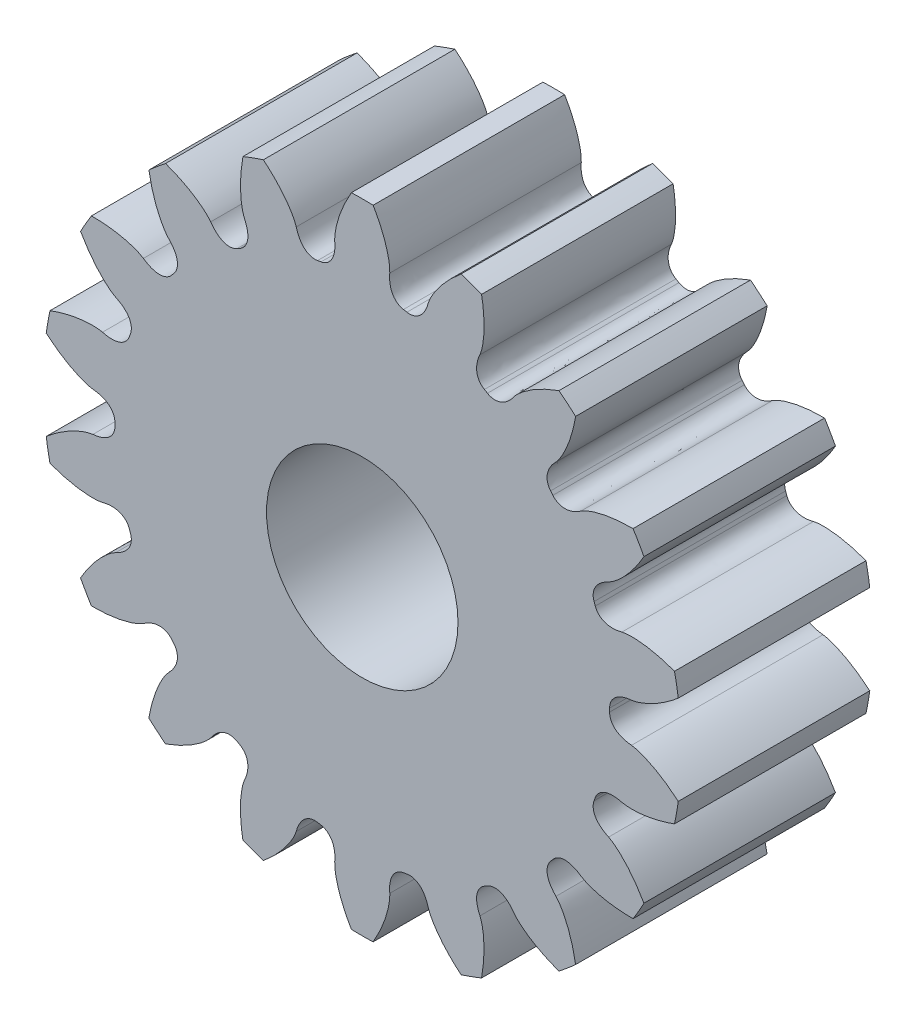
SolidWorks part; units mm, degrees
ref_plane "Спереди" through (0, 0, 0) normal (0, 0, 1) x (1, 0, 0)
ref_plane "Сверху" through (0, 0, 0) normal (0, 1, 0) x (1, 0, 0)
ref_plane "Справа" through (0, 0, 0) normal (1, 0, 0) x (0, 0, -1)
sketch "Model" plane through (0, 0, 0) normal (0, 0, 1) x (1, 0, 0)
  line L0 (-7.7, 0) -> (7.7, 0) construction
  line L1 (0, -7.7) -> (0, 7.7) construction
  arc A0 (0.1704, 4.9971) -> (-0.1704, 4.9971) centre (0, 0) ccw
  arc A1 (-0.6456, 3.8208) -> (-0.7002, 3.8112) centre (0, 0) ccw
  arc A2 (-1.549, 4.754) -> (-1.8692, 4.6375) centre (0, 0) ccw
  arc A3 (-1.9135, 3.3696) -> (-1.9614, 3.3419) centre (0, 0) ccw
  arc A4 (-3.0816, 3.9375) -> (-3.3426, 3.7185) centre (0, 0) ccw
  arc A5 (-2.9505, 2.512) -> (-2.9862, 2.4695) centre (0, 0) ccw
  arc A6 (-4.2424, 2.6461) -> (-4.4128, 2.351) centre (0, 0) ccw
  arc A7 (-3.6317, 1.3513) -> (-3.6507, 1.2993) centre (0, 0) ccw
  arc A8 (-4.8916, 1.0355) -> (-4.9508, 0.6999) centre (0, 0) ccw
  arc A9 (-3.8749, 0.0277) -> (-3.8749, -0.0277) centre (0, 0) ccw
  arc A10 (-4.9508, -0.6999) -> (-4.8916, -1.0355) centre (0, 0) ccw
  arc A11 (-3.6507, -1.2993) -> (-3.6317, -1.3513) centre (0, 0) ccw
  arc A12 (-4.4128, -2.351) -> (-4.2424, -2.6461) centre (0, 0) ccw
  arc A13 (-2.9862, -2.4695) -> (-2.9505, -2.512) centre (0, 0) ccw
  arc A14 (-3.3426, -3.7185) -> (-3.0816, -3.9375) centre (0, 0) ccw
  arc A15 (-1.9614, -3.3419) -> (-1.9135, -3.3696) centre (0, 0) ccw
  arc A16 (-1.8692, -4.6375) -> (-1.549, -4.754) centre (0, 0) ccw
  arc A17 (-0.7002, -3.8112) -> (-0.6456, -3.8208) centre (0, 0) ccw
  arc A18 (-0.1704, -4.9971) -> (0.1704, -4.9971) centre (0, 0) ccw
  arc A19 (0.6456, -3.8208) -> (0.7002, -3.8112) centre (0, 0) ccw
  arc A20 (1.549, -4.754) -> (1.8692, -4.6375) centre (0, 0) ccw
  arc A21 (1.9135, -3.3696) -> (1.9614, -3.3419) centre (0, 0) ccw
  arc A22 (3.0816, -3.9375) -> (3.3426, -3.7185) centre (0, 0) ccw
  arc A23 (2.9505, -2.512) -> (2.9862, -2.4695) centre (0, 0) ccw
  arc A24 (4.2424, -2.6461) -> (4.4128, -2.351) centre (0, 0) ccw
  arc A25 (3.6317, -1.3513) -> (3.6507, -1.2993) centre (0, 0) ccw
  arc A26 (4.8916, -1.0355) -> (4.9508, -0.6999) centre (0, 0) ccw
  arc A27 (3.8749, -0.0277) -> (3.8749, 0.0277) centre (0, 0) ccw
  arc A28 (4.9508, 0.6999) -> (4.8916, 1.0355) centre (0, 0) ccw
  arc A29 (3.6507, 1.2993) -> (3.6317, 1.3513) centre (0, 0) ccw
  arc A30 (4.4128, 2.351) -> (4.2424, 2.6461) centre (0, 0) ccw
  arc A31 (2.9862, 2.4695) -> (2.9505, 2.512) centre (0, 0) ccw
  arc A32 (3.3426, 3.7185) -> (3.0816, 3.9375) centre (0, 0) ccw
  arc A33 (1.9614, 3.3419) -> (1.9135, 3.3696) centre (0, 0) ccw
  arc A34 (1.8692, 4.6375) -> (1.549, 4.754) centre (0, 0) ccw
  arc A35 (0.7002, 3.8112) -> (0.6456, 3.8208) centre (0, 0) ccw
  circle A36 centre (0, 0) radius 4.5 construction
  spline S0 degree 3 poles (0.4314, 4.2073) (0.4264, 4.1628) (0.4271, 4.1189) (0.4335, 4.0758) (0.4372, 4.0511) (0.4421, 4.026) (0.4501, 4.0023) (0.4558, 3.9851) (0.4628, 3.968) (0.4713, 3.952) (0.4783, 3.9388) (0.4864, 3.9259) (0.4954, 3.914) (0.5034, 3.9034) (0.5123, 3.8933) (0.5218, 3.8841) (0.5307, 3.8755) (0.5403, 3.8675) (0.5504, 3.8604) (0.56, 3.8536) (0.5702, 3.8474) (0.5807, 3.8421) (0.5909, 3.837) (0.6017, 3.8326) (0.6125, 3.829) (0.6233, 3.8255) (0.6343, 3.8228) (0.6456, 3.8208) knots 0 0 0 0 1 1 1 2 2 2 3 3 3 4 4 4 5 5 5 6 6 6 7 7 7 8 8 8 9 9 9 9
  spline S1 degree 3 poles (-0.4314, 4.2073) (-0.4264, 4.1628) (-0.4271, 4.1189) (-0.4335, 4.0758) (-0.4372, 4.0511) (-0.4421, 4.026) (-0.4501, 4.0023) (-0.4558, 3.9851) (-0.4628, 3.968) (-0.4713, 3.952) (-0.4783, 3.9388) (-0.4864, 3.9259) (-0.4954, 3.914) (-0.5034, 3.9034) (-0.5123, 3.8933) (-0.5218, 3.8841) (-0.5307, 3.8755) (-0.5403, 3.8675) (-0.5504, 3.8604) (-0.56, 3.8536) (-0.5702, 3.8474) (-0.5807, 3.8421) (-0.5909, 3.837) (-0.6017, 3.8326) (-0.6125, 3.829) (-0.6233, 3.8255) (-0.6343, 3.8228) (-0.6456, 3.8208) knots 0 0 0 0 1 1 1 2 2 2 3 3 3 4 4 4 5 5 5 6 6 6 7 7 7 8 8 8 9 9 9 9
  spline S2 degree 3 poles (0.4314, 4.2073) (0.432, 4.2362) (0.431, 4.265) (0.4284, 4.2936) (0.4258, 4.3229) (0.4209, 4.352) (0.4156, 4.3809) (0.4101, 4.4104) (0.4034, 4.4397) (0.3959, 4.4687) (0.3884, 4.4983) (0.3797, 4.5277) (0.3705, 4.5568) (0.361, 4.5865) (0.3507, 4.6159) (0.3398, 4.6451) (0.3287, 4.6748) (0.3167, 4.7042) (0.3042, 4.7333) (0.2915, 4.763) (0.278, 4.7924) (0.264, 4.8215) (0.2497, 4.8511) (0.2348, 4.8805) (0.2193, 4.9095) (0.2036, 4.939) (0.1873, 4.9682) (0.1704, 4.9971) knots 0 0 0 0 1 1 1 2 2 2 3 3 3 4 4 4 5 5 5 6 6 6 7 7 7 8 8 8 9 9 9 9
  spline S3 degree 3 poles (-0.4314, 4.2073) (-0.432, 4.2362) (-0.431, 4.265) (-0.4284, 4.2936) (-0.4258, 4.3229) (-0.4209, 4.352) (-0.4156, 4.3809) (-0.4101, 4.4104) (-0.4034, 4.4397) (-0.3959, 4.4687) (-0.3884, 4.4983) (-0.3797, 4.5277) (-0.3705, 4.5568) (-0.361, 4.5865) (-0.3507, 4.6159) (-0.3398, 4.6451) (-0.3287, 4.6748) (-0.3167, 4.7042) (-0.3042, 4.7333) (-0.2915, 4.763) (-0.278, 4.7924) (-0.264, 4.8215) (-0.2497, 4.8511) (-0.2348, 4.8805) (-0.2193, 4.9095) (-0.2036, 4.939) (-0.1873, 4.9682) (-0.1704, 4.9971) knots 0 0 0 0 1 1 1 2 2 2 3 3 3 4 4 4 5 5 5 6 6 6 7 7 7 8 8 8 9 9 9 9
  spline S4 degree 3 poles (-1.0336, 4.1011) (-1.0231, 4.0576) (-1.0074, 4.0166) (-0.9866, 3.9783) (-0.9747, 3.9563) (-0.9616, 3.9344) (-0.9459, 3.9148) (-0.9346, 3.9007) (-0.9223, 3.887) (-0.9088, 3.8748) (-0.8977, 3.8649) (-0.8857, 3.8555) (-0.8732, 3.8474) (-0.862, 3.8402) (-0.8502, 3.8337) (-0.8381, 3.8283) (-0.8268, 3.8233) (-0.8151, 3.819) (-0.8032, 3.8158) (-0.7918, 3.8127) (-0.7801, 3.8104) (-0.7684, 3.809) (-0.757, 3.8077) (-0.7454, 3.8072) (-0.734, 3.8076) (-0.7227, 3.808) (-0.7114, 3.8092) (-0.7002, 3.8112) knots 0 0 0 0 1 1 1 2 2 2 3 3 3 4 4 4 5 5 5 6 6 6 7 7 7 8 8 8 9 9 9 9
  spline S5 degree 3 poles (-1.8443, 3.806) (-1.8244, 3.7659) (-1.8101, 3.7245) (-1.8014, 3.6817) (-1.7963, 3.6572) (-1.7924, 3.632) (-1.7918, 3.607) (-1.7913, 3.5888) (-1.792, 3.5704) (-1.7945, 3.5525) (-1.7966, 3.5377) (-1.7998, 3.5228) (-1.8042, 3.5085) (-1.8081, 3.4958) (-1.813, 3.4833) (-1.8188, 3.4714) (-1.8242, 3.4603) (-1.8305, 3.4495) (-1.8375, 3.4393) (-1.8442, 3.4297) (-1.8517, 3.4204) (-1.8598, 3.4118) (-1.8676, 3.4035) (-1.8762, 3.3956) (-1.8852, 3.3886) (-1.8941, 3.3816) (-1.9035, 3.3753) (-1.9135, 3.3696) knots 0 0 0 0 1 1 1 2 2 2 3 3 3 4 4 4 5 5 5 6 6 6 7 7 7 8 8 8 9 9 9 9
  spline S6 degree 3 poles (-1.0336, 4.1011) (-1.043, 4.1285) (-1.0537, 4.1552) (-1.066, 4.1812) (-1.0784, 4.2078) (-1.093, 4.2335) (-1.1079, 4.2588) (-1.123, 4.2847) (-1.1394, 4.3099) (-1.1563, 4.3346) (-1.1736, 4.3599) (-1.1917, 4.3845) (-1.2104, 4.4087) (-1.2294, 4.4334) (-1.2492, 4.4575) (-1.2694, 4.4811) (-1.29, 4.5052) (-1.3113, 4.5288) (-1.333, 4.5519) (-1.3551, 4.5755) (-1.3779, 4.5985) (-1.401, 4.621) (-1.4245, 4.644) (-1.4486, 4.6664) (-1.473, 4.6884) (-1.4979, 4.7108) (-1.5232, 4.7326) (-1.549, 4.754) knots 0 0 0 0 1 1 1 2 2 2 3 3 3 4 4 4 5 5 5 6 6 6 7 7 7 8 8 8 9 9 9 9
  spline S7 degree 3 poles (-1.8443, 3.806) (-1.8548, 3.833) (-1.8637, 3.8604) (-1.8711, 3.8882) (-1.8786, 3.9166) (-1.884, 3.9456) (-1.8889, 3.9746) (-1.8938, 4.0041) (-1.8975, 4.034) (-1.9004, 4.0638) (-1.9034, 4.0942) (-1.9054, 4.1248) (-1.9067, 4.1553) (-1.9079, 4.1864) (-1.9083, 4.2176) (-1.908, 4.2487) (-1.9077, 4.2804) (-1.9065, 4.3122) (-1.9048, 4.3438) (-1.903, 4.3761) (-1.9004, 4.4083) (-1.8971, 4.4404) (-1.8939, 4.4732) (-1.8899, 4.5058) (-1.8853, 4.5384) (-1.8806, 4.5715) (-1.8752, 4.6045) (-1.8692, 4.6375) knots 0 0 0 0 1 1 1 2 2 2 3 3 3 4 4 4 5 5 5 6 6 6 7 7 7 8 8 8 9 9 9 9
  spline S8 degree 3 poles (-2.3739, 3.5002) (-2.3491, 3.463) (-2.3204, 3.4298) (-2.2878, 3.4009) (-2.2691, 3.3843) (-2.2492, 3.3682) (-2.2278, 3.3552) (-2.2124, 3.3458) (-2.1961, 3.3371) (-2.1792, 3.3303) (-2.1654, 3.3248) (-2.151, 3.32) (-2.1364, 3.3167) (-2.1234, 3.3138) (-2.1101, 3.3117) (-2.0969, 3.3108) (-2.0846, 3.3099) (-2.0721, 3.31) (-2.0598, 3.311) (-2.0481, 3.312) (-2.0363, 3.3138) (-2.0248, 3.3165) (-2.0137, 3.3191) (-2.0026, 3.3226) (-1.992, 3.3269) (-1.9815, 3.3311) (-1.9713, 3.3361) (-1.9614, 3.3419) knots 0 0 0 0 1 1 1 2 2 2 3 3 3 4 4 4 5 5 5 6 6 6 7 7 7 8 8 8 9 9 9 9
  spline S9 degree 3 poles (-3.0348, 2.9457) (-3.0024, 2.9148) (-2.9748, 2.8807) (-2.952, 2.8436) (-2.9389, 2.8223) (-2.9265, 2.7999) (-2.9174, 2.7766) (-2.9108, 2.7597) (-2.9051, 2.7422) (-2.9013, 2.7245) (-2.8982, 2.7098) (-2.8961, 2.6948) (-2.8954, 2.6799) (-2.8947, 2.6666) (-2.895, 2.6531) (-2.8964, 2.6399) (-2.8977, 2.6277) (-2.8999, 2.6154) (-2.903, 2.6035) (-2.906, 2.5921) (-2.9098, 2.5808) (-2.9145, 2.57) (-2.919, 2.5595) (-2.9244, 2.5492) (-2.9305, 2.5394) (-2.9364, 2.5298) (-2.9431, 2.5207) (-2.9505, 2.512) knots 0 0 0 0 1 1 1 2 2 2 3 3 3 4 4 4 5 5 5 6 6 6 7 7 7 8 8 8 9 9 9 9
  spline S10 degree 3 poles (-2.3739, 3.5002) (-2.3921, 3.5228) (-2.4113, 3.5442) (-2.4317, 3.5645) (-2.4525, 3.5852) (-2.475, 3.6044) (-2.4977, 3.6231) (-2.5208, 3.6422) (-2.5448, 3.6603) (-2.5691, 3.6777) (-2.594, 3.6955) (-2.6195, 3.7125) (-2.6453, 3.7289) (-2.6716, 3.7455) (-2.6984, 3.7614) (-2.7255, 3.7767) (-2.7531, 3.7923) (-2.7812, 3.8072) (-2.8095, 3.8215) (-2.8383, 3.836) (-2.8675, 3.8499) (-2.897, 3.8632) (-2.9269, 3.8767) (-2.9572, 3.8896) (-2.9877, 3.9019) (-3.0187, 3.9144) (-3.05, 3.9263) (-3.0816, 3.9375) knots 0 0 0 0 1 1 1 2 2 2 3 3 3 4 4 4 5 5 5 6 6 6 7 7 7 8 8 8 9 9 9 9
  spline S11 degree 3 poles (-3.0348, 2.9457) (-3.0539, 2.9675) (-3.0716, 2.9902) (-3.0881, 3.0137) (-3.1049, 3.0378) (-3.1199, 3.0633) (-3.1343, 3.0889) (-3.1491, 3.1149) (-3.1627, 3.1417) (-3.1757, 3.1687) (-3.189, 3.1963) (-3.2012, 3.2243) (-3.2129, 3.2526) (-3.2247, 3.2814) (-3.2357, 3.3106) (-3.2461, 3.3399) (-3.2566, 3.3698) (-3.2664, 3.4) (-3.2756, 3.4304) (-3.2849, 3.4613) (-3.2935, 3.4925) (-3.3015, 3.5238) (-3.3096, 3.5557) (-3.317, 3.5877) (-3.3238, 3.6199) (-3.3307, 3.6526) (-3.337, 3.6855) (-3.3426, 3.7185) knots 0 0 0 0 1 1 1 2 2 2 3 3 3 4 4 4 5 5 5 6 6 6 7 7 7 8 8 8 9 9 9 9
  spline S12 degree 3 poles (-3.4279, 2.4772) (-3.3919, 2.4507) (-3.3535, 2.4294) (-3.313, 2.4133) (-3.2897, 2.4041) (-3.2656, 2.3958) (-3.241, 2.3909) (-3.2233, 2.3873) (-3.205, 2.3848) (-3.1869, 2.3842) (-3.1719, 2.3837) (-3.1568, 2.3841) (-3.1419, 2.386) (-3.1288, 2.3877) (-3.1155, 2.3903) (-3.1028, 2.3939) (-3.0909, 2.3974) (-3.0792, 2.4017) (-3.068, 2.4068) (-3.0573, 2.4117) (-3.0469, 2.4175) (-3.037, 2.424) (-3.0275, 2.4303) (-3.0183, 2.4373) (-3.0097, 2.445) (-3.0013, 2.4525) (-2.9935, 2.4607) (-2.9862, 2.4695) knots 0 0 0 0 1 1 1 2 2 2 3 3 3 4 4 4 5 5 5 6 6 6 7 7 7 8 8 8 9 9 9 9
  spline S13 degree 3 poles (-3.8593, 1.7301) (-3.8183, 1.7121) (-3.7807, 1.6896) (-3.7465, 1.6625) (-3.7269, 1.6469) (-3.7076, 1.6301) (-3.6911, 1.6114) (-3.6791, 1.5978) (-3.6678, 1.5832) (-3.6582, 1.5678) (-3.6503, 1.5551) (-3.6431, 1.5418) (-3.6373, 1.528) (-3.6322, 1.5157) (-3.6278, 1.503) (-3.6246, 1.4901) (-3.6216, 1.4782) (-3.6195, 1.4658) (-3.6184, 1.4536) (-3.6173, 1.4419) (-3.617, 1.4299) (-3.6177, 1.4182) (-3.6184, 1.4067) (-3.6199, 1.3952) (-3.6223, 1.384) (-3.6246, 1.373) (-3.6278, 1.3621) (-3.6317, 1.3513) knots 0 0 0 0 1 1 1 2 2 2 3 3 3 4 4 4 5 5 5 6 6 6 7 7 7 8 8 8 9 9 9 9
  spline S14 degree 3 poles (-3.4279, 2.4772) (-3.4527, 2.4922) (-3.4781, 2.5057) (-3.5042, 2.5178) (-3.5308, 2.5302) (-3.5585, 2.5405) (-3.5862, 2.5504) (-3.6144, 2.5604) (-3.6432, 2.5691) (-3.6721, 2.5772) (-3.7015, 2.5855) (-3.7312, 2.5927) (-3.7611, 2.5992) (-3.7915, 2.6059) (-3.8221, 2.6117) (-3.8529, 2.6168) (-3.8841, 2.622) (-3.9156, 2.6264) (-3.9471, 2.6301) (-3.9792, 2.6339) (-4.0113, 2.637) (-4.0436, 2.6394) (-4.0763, 2.6419) (-4.1092, 2.6436) (-4.1421, 2.6447) (-4.1755, 2.6458) (-4.2089, 2.6463) (-4.2424, 2.6461) knots 0 0 0 0 1 1 1 2 2 2 3 3 3 4 4 4 5 5 5 6 6 6 7 7 7 8 8 8 9 9 9 9
  spline S15 degree 3 poles (-3.8593, 1.7301) (-3.8846, 1.744) (-3.9091, 1.7593) (-3.9326, 1.7758) (-3.9566, 1.7927) (-3.9794, 1.8115) (-4.0018, 1.8306) (-4.0246, 1.85) (-4.0465, 1.8705) (-4.068, 1.8915) (-4.0898, 1.9128) (-4.111, 1.935) (-4.1316, 1.9576) (-4.1525, 1.9806) (-4.1729, 2.0042) (-4.1926, 2.0283) (-4.2128, 2.0528) (-4.2323, 2.0778) (-4.2513, 2.1032) (-4.2706, 2.1291) (-4.2894, 2.1554) (-4.3076, 2.1821) (-4.3261, 2.2093) (-4.344, 2.2369) (-4.3614, 2.2648) (-4.3791, 2.2932) (-4.3962, 2.3219) (-4.4128, 2.351) knots 0 0 0 0 1 1 1 2 2 2 3 3 3 4 4 4 5 5 5 6 6 6 7 7 7 8 8 8 9 9 9 9
  spline S16 degree 3 poles (-4.0684, 1.1554) (-4.0255, 1.1428) (-3.9822, 1.1359) (-3.9386, 1.1347) (-3.9136, 1.134) (-3.888, 1.1345) (-3.8633, 1.1382) (-3.8454, 1.1409) (-3.8273, 1.1448) (-3.8101, 1.1504) (-3.7959, 1.155) (-3.7818, 1.1607) (-3.7685, 1.1675) (-3.7567, 1.1736) (-3.7452, 1.1806) (-3.7344, 1.1884) (-3.7245, 1.1956) (-3.7149, 1.2037) (-3.7062, 1.2123) (-3.6978, 1.2206) (-3.69, 1.2296) (-3.6829, 1.239) (-3.6761, 1.2482) (-3.6699, 1.258) (-3.6645, 1.2681) (-3.6591, 1.2781) (-3.6545, 1.2885) (-3.6507, 1.2993) knots 0 0 0 0 1 1 1 2 2 2 3 3 3 4 4 4 5 5 5 6 6 6 7 7 7 8 8 8 9 9 9 9
  spline S17 degree 3 poles (-4.2183, 0.3058) (-4.1736, 0.3029) (-4.1305, 0.2946) (-4.0892, 0.2808) (-4.0654, 0.2729) (-4.0416, 0.2637) (-4.0196, 0.2518) (-4.0037, 0.2431) (-3.9881, 0.2333) (-3.9738, 0.2221) (-3.962, 0.2129) (-3.9507, 0.2028) (-3.9406, 0.1918) (-3.9315, 0.1821) (-3.9231, 0.1716) (-3.9157, 0.1606) (-3.9088, 0.1503) (-3.9026, 0.1395) (-3.8973, 0.1284) (-3.8923, 0.1177) (-3.888, 0.1066) (-3.8846, 0.0953) (-3.8813, 0.0843) (-3.8788, 0.073) (-3.8772, 0.0617) (-3.8756, 0.0505) (-3.8748, 0.0391) (-3.8749, 0.0277) knots 0 0 0 0 1 1 1 2 2 2 3 3 3 4 4 4 5 5 5 6 6 6 7 7 7 8 8 8 9 9 9 9
  spline S18 degree 3 poles (-4.0684, 1.1554) (-4.0968, 1.161) (-4.1254, 1.165) (-4.154, 1.1675) (-4.1833, 1.17) (-4.2128, 1.1702) (-4.2422, 1.17) (-4.2722, 1.1698) (-4.3022, 1.1682) (-4.3321, 1.1659) (-4.3625, 1.1636) (-4.393, 1.1602) (-4.4232, 1.1561) (-4.4541, 1.152) (-4.4849, 1.1469) (-4.5155, 1.1412) (-4.5467, 1.1354) (-4.5777, 1.1288) (-4.6086, 1.1215) (-4.64, 1.1141) (-4.6713, 1.106) (-4.7024, 1.0972) (-4.7341, 1.0883) (-4.7655, 1.0787) (-4.7968, 1.0685) (-4.8286, 1.0582) (-4.8602, 1.0472) (-4.8916, 1.0355) knots 0 0 0 0 1 1 1 2 2 2 3 3 3 4 4 4 5 5 5 6 6 6 7 7 7 8 8 8 9 9 9 9
  spline S19 degree 3 poles (-4.2183, 0.3058) (-4.2468, 0.3102) (-4.275, 0.3162) (-4.3028, 0.3237) (-4.3311, 0.3314) (-4.359, 0.3412) (-4.3865, 0.3515) (-4.4146, 0.362) (-4.4423, 0.3737) (-4.4696, 0.3861) (-4.4974, 0.3987) (-4.5248, 0.4123) (-4.5519, 0.4264) (-4.5795, 0.4409) (-4.6067, 0.4562) (-4.6335, 0.472) (-4.6608, 0.4881) (-4.6877, 0.505) (-4.7143, 0.5223) (-4.7413, 0.54) (-4.7679, 0.5584) (-4.7941, 0.5773) (-4.8208, 0.5964) (-4.8471, 0.6162) (-4.873, 0.6365) (-4.8993, 0.6571) (-4.9252, 0.6783) (-4.9508, 0.6999) knots 0 0 0 0 1 1 1 2 2 2 3 3 3 4 4 4 5 5 5 6 6 6 7 7 7 8 8 8 9 9 9 9
  spline S20 degree 3 poles (-4.2183, -0.3058) (-4.1736, -0.3029) (-4.1305, -0.2946) (-4.0892, -0.2808) (-4.0654, -0.2729) (-4.0416, -0.2637) (-4.0196, -0.2518) (-4.0037, -0.2431) (-3.9881, -0.2333) (-3.9738, -0.2221) (-3.962, -0.2129) (-3.9507, -0.2028) (-3.9406, -0.1918) (-3.9315, -0.1821) (-3.9231, -0.1716) (-3.9157, -0.1606) (-3.9088, -0.1503) (-3.9026, -0.1395) (-3.8973, -0.1284) (-3.8923, -0.1177) (-3.888, -0.1066) (-3.8846, -0.0953) (-3.8813, -0.0843) (-3.8788, -0.073) (-3.8772, -0.0617) (-3.8756, -0.0505) (-3.8748, -0.0391) (-3.8749, -0.0277) knots 0 0 0 0 1 1 1 2 2 2 3 3 3 4 4 4 5 5 5 6 6 6 7 7 7 8 8 8 9 9 9 9
  spline S21 degree 3 poles (-4.0684, -1.1554) (-4.0255, -1.1428) (-3.9822, -1.1359) (-3.9386, -1.1347) (-3.9136, -1.134) (-3.888, -1.1345) (-3.8633, -1.1382) (-3.8454, -1.1409) (-3.8273, -1.1448) (-3.8101, -1.1504) (-3.7959, -1.155) (-3.7818, -1.1607) (-3.7685, -1.1675) (-3.7567, -1.1736) (-3.7452, -1.1806) (-3.7344, -1.1884) (-3.7245, -1.1956) (-3.7149, -1.2037) (-3.7062, -1.2123) (-3.6978, -1.2206) (-3.69, -1.2296) (-3.6829, -1.239) (-3.6761, -1.2482) (-3.6699, -1.258) (-3.6645, -1.2681) (-3.6591, -1.2781) (-3.6545, -1.2885) (-3.6507, -1.2993) knots 0 0 0 0 1 1 1 2 2 2 3 3 3 4 4 4 5 5 5 6 6 6 7 7 7 8 8 8 9 9 9 9
  spline S22 degree 3 poles (-4.2183, -0.3058) (-4.2468, -0.3102) (-4.275, -0.3162) (-4.3028, -0.3237) (-4.3311, -0.3314) (-4.359, -0.3412) (-4.3865, -0.3515) (-4.4146, -0.362) (-4.4423, -0.3737) (-4.4696, -0.3861) (-4.4974, -0.3987) (-4.5248, -0.4123) (-4.5519, -0.4264) (-4.5795, -0.4409) (-4.6067, -0.4562) (-4.6335, -0.472) (-4.6608, -0.4881) (-4.6877, -0.505) (-4.7143, -0.5223) (-4.7413, -0.54) (-4.7679, -0.5584) (-4.7941, -0.5773) (-4.8208, -0.5964) (-4.8471, -0.6162) (-4.873, -0.6365) (-4.8993, -0.6571) (-4.9252, -0.6783) (-4.9508, -0.6999) knots 0 0 0 0 1 1 1 2 2 2 3 3 3 4 4 4 5 5 5 6 6 6 7 7 7 8 8 8 9 9 9 9
  spline S23 degree 3 poles (-4.0684, -1.1554) (-4.0968, -1.161) (-4.1254, -1.165) (-4.154, -1.1675) (-4.1833, -1.17) (-4.2128, -1.1702) (-4.2422, -1.17) (-4.2722, -1.1698) (-4.3022, -1.1682) (-4.3321, -1.1659) (-4.3625, -1.1636) (-4.393, -1.1602) (-4.4232, -1.1561) (-4.4541, -1.152) (-4.4849, -1.1469) (-4.5155, -1.1412) (-4.5467, -1.1354) (-4.5777, -1.1288) (-4.6086, -1.1215) (-4.64, -1.1141) (-4.6713, -1.106) (-4.7024, -1.0972) (-4.7341, -1.0883) (-4.7655, -1.0787) (-4.7968, -1.0685) (-4.8286, -1.0582) (-4.8602, -1.0472) (-4.8916, -1.0355) knots 0 0 0 0 1 1 1 2 2 2 3 3 3 4 4 4 5 5 5 6 6 6 7 7 7 8 8 8 9 9 9 9
  spline S24 degree 3 poles (-3.8593, -1.7301) (-3.8183, -1.7121) (-3.7807, -1.6896) (-3.7465, -1.6625) (-3.7269, -1.6469) (-3.7076, -1.6301) (-3.6911, -1.6114) (-3.6791, -1.5978) (-3.6678, -1.5832) (-3.6582, -1.5678) (-3.6503, -1.5551) (-3.6431, -1.5418) (-3.6373, -1.528) (-3.6322, -1.5157) (-3.6278, -1.503) (-3.6246, -1.4901) (-3.6216, -1.4782) (-3.6195, -1.4658) (-3.6184, -1.4536) (-3.6173, -1.4419) (-3.617, -1.4299) (-3.6177, -1.4182) (-3.6184, -1.4067) (-3.6199, -1.3952) (-3.6223, -1.384) (-3.6246, -1.373) (-3.6278, -1.3621) (-3.6317, -1.3513) knots 0 0 0 0 1 1 1 2 2 2 3 3 3 4 4 4 5 5 5 6 6 6 7 7 7 8 8 8 9 9 9 9
  spline S25 degree 3 poles (-3.4279, -2.4772) (-3.3919, -2.4507) (-3.3535, -2.4294) (-3.313, -2.4133) (-3.2897, -2.4041) (-3.2656, -2.3958) (-3.241, -2.3909) (-3.2233, -2.3873) (-3.205, -2.3848) (-3.1869, -2.3842) (-3.1719, -2.3837) (-3.1568, -2.3841) (-3.1419, -2.386) (-3.1288, -2.3877) (-3.1155, -2.3903) (-3.1028, -2.3939) (-3.0909, -2.3974) (-3.0792, -2.4017) (-3.068, -2.4068) (-3.0573, -2.4117) (-3.0469, -2.4175) (-3.037, -2.424) (-3.0275, -2.4303) (-3.0183, -2.4373) (-3.0097, -2.445) (-3.0013, -2.4525) (-2.9935, -2.4607) (-2.9862, -2.4695) knots 0 0 0 0 1 1 1 2 2 2 3 3 3 4 4 4 5 5 5 6 6 6 7 7 7 8 8 8 9 9 9 9
  spline S26 degree 3 poles (-3.8593, -1.7301) (-3.8846, -1.744) (-3.9091, -1.7593) (-3.9326, -1.7758) (-3.9566, -1.7927) (-3.9794, -1.8115) (-4.0018, -1.8306) (-4.0246, -1.85) (-4.0465, -1.8705) (-4.068, -1.8915) (-4.0898, -1.9128) (-4.111, -1.935) (-4.1316, -1.9576) (-4.1525, -1.9806) (-4.1729, -2.0042) (-4.1926, -2.0283) (-4.2128, -2.0528) (-4.2323, -2.0778) (-4.2513, -2.1032) (-4.2706, -2.1291) (-4.2894, -2.1554) (-4.3076, -2.1821) (-4.3261, -2.2093) (-4.344, -2.2369) (-4.3614, -2.2648) (-4.3791, -2.2932) (-4.3962, -2.3219) (-4.4128, -2.351) knots 0 0 0 0 1 1 1 2 2 2 3 3 3 4 4 4 5 5 5 6 6 6 7 7 7 8 8 8 9 9 9 9
  spline S27 degree 3 poles (-3.4279, -2.4772) (-3.4527, -2.4922) (-3.4781, -2.5057) (-3.5042, -2.5178) (-3.5308, -2.5302) (-3.5585, -2.5405) (-3.5862, -2.5504) (-3.6144, -2.5604) (-3.6432, -2.5691) (-3.6721, -2.5772) (-3.7015, -2.5855) (-3.7312, -2.5927) (-3.7611, -2.5992) (-3.7915, -2.6059) (-3.8221, -2.6117) (-3.8529, -2.6168) (-3.8841, -2.622) (-3.9156, -2.6264) (-3.9471, -2.6301) (-3.9792, -2.6339) (-4.0113, -2.637) (-4.0436, -2.6394) (-4.0763, -2.6419) (-4.1092, -2.6436) (-4.1421, -2.6447) (-4.1755, -2.6458) (-4.2089, -2.6463) (-4.2424, -2.6461) knots 0 0 0 0 1 1 1 2 2 2 3 3 3 4 4 4 5 5 5 6 6 6 7 7 7 8 8 8 9 9 9 9
  spline S28 degree 3 poles (-3.0348, -2.9457) (-3.0024, -2.9148) (-2.9748, -2.8807) (-2.952, -2.8436) (-2.9389, -2.8223) (-2.9265, -2.7999) (-2.9174, -2.7766) (-2.9108, -2.7597) (-2.9051, -2.7422) (-2.9013, -2.7245) (-2.8982, -2.7098) (-2.8961, -2.6948) (-2.8954, -2.6799) (-2.8947, -2.6666) (-2.895, -2.6531) (-2.8964, -2.6399) (-2.8977, -2.6277) (-2.8999, -2.6154) (-2.903, -2.6035) (-2.906, -2.5921) (-2.9098, -2.5808) (-2.9145, -2.57) (-2.919, -2.5595) (-2.9244, -2.5492) (-2.9305, -2.5394) (-2.9364, -2.5298) (-2.9431, -2.5207) (-2.9505, -2.512) knots 0 0 0 0 1 1 1 2 2 2 3 3 3 4 4 4 5 5 5 6 6 6 7 7 7 8 8 8 9 9 9 9
  spline S29 degree 3 poles (-2.3739, -3.5002) (-2.3491, -3.463) (-2.3204, -3.4298) (-2.2878, -3.4009) (-2.2691, -3.3843) (-2.2492, -3.3682) (-2.2278, -3.3552) (-2.2124, -3.3458) (-2.1961, -3.3371) (-2.1792, -3.3303) (-2.1654, -3.3248) (-2.151, -3.32) (-2.1364, -3.3167) (-2.1234, -3.3138) (-2.1101, -3.3117) (-2.0969, -3.3108) (-2.0846, -3.3099) (-2.0721, -3.31) (-2.0598, -3.311) (-2.0481, -3.312) (-2.0363, -3.3138) (-2.0248, -3.3165) (-2.0137, -3.3191) (-2.0026, -3.3226) (-1.992, -3.3269) (-1.9815, -3.3311) (-1.9713, -3.3361) (-1.9614, -3.3419) knots 0 0 0 0 1 1 1 2 2 2 3 3 3 4 4 4 5 5 5 6 6 6 7 7 7 8 8 8 9 9 9 9
  spline S30 degree 3 poles (-3.0348, -2.9457) (-3.0539, -2.9675) (-3.0716, -2.9902) (-3.0881, -3.0137) (-3.1049, -3.0378) (-3.1199, -3.0633) (-3.1343, -3.0889) (-3.1491, -3.1149) (-3.1627, -3.1417) (-3.1757, -3.1687) (-3.189, -3.1963) (-3.2012, -3.2243) (-3.2129, -3.2526) (-3.2247, -3.2814) (-3.2357, -3.3106) (-3.2461, -3.3399) (-3.2566, -3.3698) (-3.2664, -3.4) (-3.2756, -3.4304) (-3.2849, -3.4613) (-3.2935, -3.4925) (-3.3015, -3.5238) (-3.3096, -3.5557) (-3.317, -3.5877) (-3.3238, -3.6199) (-3.3307, -3.6526) (-3.337, -3.6855) (-3.3426, -3.7185) knots 0 0 0 0 1 1 1 2 2 2 3 3 3 4 4 4 5 5 5 6 6 6 7 7 7 8 8 8 9 9 9 9
  spline S31 degree 3 poles (-2.3739, -3.5002) (-2.3921, -3.5228) (-2.4113, -3.5442) (-2.4317, -3.5645) (-2.4525, -3.5852) (-2.475, -3.6044) (-2.4977, -3.6231) (-2.5208, -3.6422) (-2.5448, -3.6603) (-2.5691, -3.6777) (-2.594, -3.6955) (-2.6195, -3.7125) (-2.6453, -3.7289) (-2.6716, -3.7455) (-2.6984, -3.7614) (-2.7255, -3.7767) (-2.7531, -3.7923) (-2.7812, -3.8072) (-2.8095, -3.8215) (-2.8383, -3.836) (-2.8675, -3.8499) (-2.897, -3.8632) (-2.9269, -3.8767) (-2.9572, -3.8896) (-2.9877, -3.9019) (-3.0187, -3.9144) (-3.05, -3.9263) (-3.0816, -3.9375) knots 0 0 0 0 1 1 1 2 2 2 3 3 3 4 4 4 5 5 5 6 6 6 7 7 7 8 8 8 9 9 9 9
  spline S32 degree 3 poles (-1.8443, -3.806) (-1.8244, -3.7659) (-1.8101, -3.7245) (-1.8014, -3.6817) (-1.7963, -3.6572) (-1.7924, -3.632) (-1.7918, -3.607) (-1.7913, -3.5888) (-1.792, -3.5704) (-1.7945, -3.5525) (-1.7966, -3.5377) (-1.7998, -3.5228) (-1.8042, -3.5085) (-1.8081, -3.4958) (-1.813, -3.4833) (-1.8188, -3.4714) (-1.8242, -3.4603) (-1.8305, -3.4495) (-1.8375, -3.4393) (-1.8442, -3.4297) (-1.8517, -3.4204) (-1.8598, -3.4118) (-1.8676, -3.4035) (-1.8762, -3.3956) (-1.8852, -3.3886) (-1.8941, -3.3816) (-1.9035, -3.3753) (-1.9135, -3.3696) knots 0 0 0 0 1 1 1 2 2 2 3 3 3 4 4 4 5 5 5 6 6 6 7 7 7 8 8 8 9 9 9 9
  spline S33 degree 3 poles (-1.0336, -4.1011) (-1.0231, -4.0576) (-1.0074, -4.0166) (-0.9866, -3.9783) (-0.9747, -3.9563) (-0.9616, -3.9344) (-0.9459, -3.9148) (-0.9346, -3.9007) (-0.9223, -3.887) (-0.9088, -3.8748) (-0.8977, -3.8649) (-0.8857, -3.8555) (-0.8732, -3.8474) (-0.862, -3.8402) (-0.8502, -3.8337) (-0.8381, -3.8283) (-0.8268, -3.8233) (-0.8151, -3.819) (-0.8032, -3.8158) (-0.7918, -3.8127) (-0.7801, -3.8104) (-0.7684, -3.809) (-0.757, -3.8077) (-0.7454, -3.8072) (-0.734, -3.8076) (-0.7227, -3.808) (-0.7114, -3.8092) (-0.7002, -3.8112) knots 0 0 0 0 1 1 1 2 2 2 3 3 3 4 4 4 5 5 5 6 6 6 7 7 7 8 8 8 9 9 9 9
  spline S34 degree 3 poles (-1.8443, -3.806) (-1.8548, -3.833) (-1.8637, -3.8604) (-1.8711, -3.8882) (-1.8786, -3.9166) (-1.884, -3.9456) (-1.8889, -3.9746) (-1.8938, -4.0041) (-1.8975, -4.034) (-1.9004, -4.0638) (-1.9034, -4.0942) (-1.9054, -4.1248) (-1.9067, -4.1553) (-1.9079, -4.1864) (-1.9083, -4.2176) (-1.908, -4.2487) (-1.9077, -4.2804) (-1.9065, -4.3122) (-1.9048, -4.3438) (-1.903, -4.3761) (-1.9004, -4.4083) (-1.8971, -4.4404) (-1.8939, -4.4732) (-1.8899, -4.5058) (-1.8853, -4.5384) (-1.8806, -4.5715) (-1.8752, -4.6045) (-1.8692, -4.6375) knots 0 0 0 0 1 1 1 2 2 2 3 3 3 4 4 4 5 5 5 6 6 6 7 7 7 8 8 8 9 9 9 9
  spline S35 degree 3 poles (-1.0336, -4.1011) (-1.043, -4.1285) (-1.0537, -4.1552) (-1.066, -4.1812) (-1.0784, -4.2078) (-1.093, -4.2335) (-1.1079, -4.2588) (-1.123, -4.2847) (-1.1394, -4.3099) (-1.1563, -4.3346) (-1.1736, -4.3599) (-1.1917, -4.3845) (-1.2104, -4.4087) (-1.2294, -4.4334) (-1.2492, -4.4575) (-1.2694, -4.4811) (-1.29, -4.5052) (-1.3113, -4.5288) (-1.333, -4.5519) (-1.3551, -4.5755) (-1.3779, -4.5985) (-1.401, -4.621) (-1.4245, -4.644) (-1.4486, -4.6664) (-1.473, -4.6884) (-1.4979, -4.7108) (-1.5232, -4.7326) (-1.549, -4.754) knots 0 0 0 0 1 1 1 2 2 2 3 3 3 4 4 4 5 5 5 6 6 6 7 7 7 8 8 8 9 9 9 9
  spline S36 degree 3 poles (-0.4314, -4.2073) (-0.4264, -4.1628) (-0.4271, -4.1189) (-0.4335, -4.0758) (-0.4372, -4.0511) (-0.4421, -4.026) (-0.4501, -4.0023) (-0.4558, -3.9851) (-0.4628, -3.968) (-0.4713, -3.952) (-0.4783, -3.9388) (-0.4864, -3.9259) (-0.4954, -3.914) (-0.5034, -3.9034) (-0.5123, -3.8933) (-0.5218, -3.8841) (-0.5307, -3.8755) (-0.5403, -3.8675) (-0.5504, -3.8604) (-0.56, -3.8536) (-0.5702, -3.8474) (-0.5807, -3.8421) (-0.5909, -3.837) (-0.6017, -3.8326) (-0.6125, -3.829) (-0.6233, -3.8255) (-0.6343, -3.8228) (-0.6456, -3.8208) knots 0 0 0 0 1 1 1 2 2 2 3 3 3 4 4 4 5 5 5 6 6 6 7 7 7 8 8 8 9 9 9 9
  spline S37 degree 3 poles (0.4314, -4.2073) (0.4264, -4.1628) (0.4271, -4.1189) (0.4335, -4.0758) (0.4372, -4.0511) (0.4421, -4.026) (0.4501, -4.0023) (0.4558, -3.9851) (0.4628, -3.968) (0.4713, -3.952) (0.4783, -3.9388) (0.4864, -3.9259) (0.4954, -3.914) (0.5034, -3.9034) (0.5123, -3.8933) (0.5218, -3.8841) (0.5307, -3.8755) (0.5403, -3.8675) (0.5504, -3.8604) (0.56, -3.8536) (0.5702, -3.8474) (0.5807, -3.8421) (0.5909, -3.837) (0.6017, -3.8326) (0.6125, -3.829) (0.6233, -3.8255) (0.6343, -3.8228) (0.6456, -3.8208) knots 0 0 0 0 1 1 1 2 2 2 3 3 3 4 4 4 5 5 5 6 6 6 7 7 7 8 8 8 9 9 9 9
  spline S38 degree 3 poles (-0.4314, -4.2073) (-0.432, -4.2362) (-0.431, -4.265) (-0.4284, -4.2936) (-0.4258, -4.3229) (-0.4209, -4.352) (-0.4156, -4.3809) (-0.4101, -4.4104) (-0.4034, -4.4397) (-0.3959, -4.4687) (-0.3884, -4.4983) (-0.3797, -4.5277) (-0.3705, -4.5568) (-0.361, -4.5865) (-0.3507, -4.6159) (-0.3398, -4.6451) (-0.3287, -4.6748) (-0.3167, -4.7042) (-0.3042, -4.7333) (-0.2915, -4.763) (-0.278, -4.7924) (-0.264, -4.8215) (-0.2497, -4.8511) (-0.2348, -4.8805) (-0.2193, -4.9095) (-0.2036, -4.939) (-0.1873, -4.9682) (-0.1704, -4.9971) knots 0 0 0 0 1 1 1 2 2 2 3 3 3 4 4 4 5 5 5 6 6 6 7 7 7 8 8 8 9 9 9 9
  spline S39 degree 3 poles (0.4314, -4.2073) (0.432, -4.2362) (0.431, -4.265) (0.4284, -4.2936) (0.4258, -4.3229) (0.4209, -4.352) (0.4156, -4.3809) (0.4101, -4.4104) (0.4034, -4.4397) (0.3959, -4.4687) (0.3884, -4.4983) (0.3797, -4.5277) (0.3705, -4.5568) (0.361, -4.5865) (0.3507, -4.6159) (0.3398, -4.6451) (0.3287, -4.6748) (0.3167, -4.7042) (0.3042, -4.7333) (0.2915, -4.763) (0.278, -4.7924) (0.264, -4.8215) (0.2497, -4.8511) (0.2348, -4.8805) (0.2193, -4.9095) (0.2036, -4.939) (0.1873, -4.9682) (0.1704, -4.9971) knots 0 0 0 0 1 1 1 2 2 2 3 3 3 4 4 4 5 5 5 6 6 6 7 7 7 8 8 8 9 9 9 9
  spline S40 degree 3 poles (1.0336, -4.1011) (1.0231, -4.0576) (1.0074, -4.0166) (0.9866, -3.9783) (0.9747, -3.9563) (0.9616, -3.9344) (0.9459, -3.9148) (0.9346, -3.9007) (0.9223, -3.887) (0.9088, -3.8748) (0.8977, -3.8649) (0.8857, -3.8555) (0.8732, -3.8474) (0.862, -3.8402) (0.8502, -3.8337) (0.8381, -3.8283) (0.8268, -3.8233) (0.8151, -3.819) (0.8032, -3.8158) (0.7918, -3.8127) (0.7801, -3.8104) (0.7684, -3.809) (0.757, -3.8077) (0.7454, -3.8072) (0.734, -3.8076) (0.7227, -3.808) (0.7114, -3.8092) (0.7002, -3.8112) knots 0 0 0 0 1 1 1 2 2 2 3 3 3 4 4 4 5 5 5 6 6 6 7 7 7 8 8 8 9 9 9 9
  spline S41 degree 3 poles (1.8443, -3.806) (1.8244, -3.7659) (1.8101, -3.7245) (1.8014, -3.6817) (1.7963, -3.6572) (1.7924, -3.632) (1.7918, -3.607) (1.7913, -3.5888) (1.792, -3.5704) (1.7945, -3.5525) (1.7966, -3.5377) (1.7998, -3.5228) (1.8042, -3.5085) (1.8081, -3.4958) (1.813, -3.4833) (1.8188, -3.4714) (1.8242, -3.4603) (1.8305, -3.4495) (1.8375, -3.4393) (1.8442, -3.4297) (1.8517, -3.4204) (1.8598, -3.4118) (1.8676, -3.4035) (1.8762, -3.3956) (1.8852, -3.3886) (1.8941, -3.3816) (1.9035, -3.3753) (1.9135, -3.3696) knots 0 0 0 0 1 1 1 2 2 2 3 3 3 4 4 4 5 5 5 6 6 6 7 7 7 8 8 8 9 9 9 9
  spline S42 degree 3 poles (1.0336, -4.1011) (1.043, -4.1285) (1.0537, -4.1552) (1.066, -4.1812) (1.0784, -4.2078) (1.093, -4.2335) (1.1079, -4.2588) (1.123, -4.2847) (1.1394, -4.3099) (1.1563, -4.3346) (1.1736, -4.3599) (1.1917, -4.3845) (1.2104, -4.4087) (1.2294, -4.4334) (1.2492, -4.4575) (1.2694, -4.4811) (1.29, -4.5052) (1.3113, -4.5288) (1.333, -4.5519) (1.3551, -4.5755) (1.3779, -4.5985) (1.401, -4.621) (1.4245, -4.644) (1.4486, -4.6664) (1.473, -4.6884) (1.4979, -4.7108) (1.5232, -4.7326) (1.549, -4.754) knots 0 0 0 0 1 1 1 2 2 2 3 3 3 4 4 4 5 5 5 6 6 6 7 7 7 8 8 8 9 9 9 9
  spline S43 degree 3 poles (1.8443, -3.806) (1.8548, -3.833) (1.8637, -3.8604) (1.8711, -3.8882) (1.8786, -3.9166) (1.884, -3.9456) (1.8889, -3.9746) (1.8938, -4.0041) (1.8975, -4.034) (1.9004, -4.0638) (1.9034, -4.0942) (1.9054, -4.1248) (1.9067, -4.1553) (1.9079, -4.1864) (1.9083, -4.2176) (1.908, -4.2487) (1.9077, -4.2804) (1.9065, -4.3122) (1.9048, -4.3438) (1.903, -4.3761) (1.9004, -4.4083) (1.8971, -4.4404) (1.8939, -4.4732) (1.8899, -4.5058) (1.8853, -4.5384) (1.8806, -4.5715) (1.8752, -4.6045) (1.8692, -4.6375) knots 0 0 0 0 1 1 1 2 2 2 3 3 3 4 4 4 5 5 5 6 6 6 7 7 7 8 8 8 9 9 9 9
  spline S44 degree 3 poles (2.3739, -3.5002) (2.3491, -3.463) (2.3204, -3.4298) (2.2878, -3.4009) (2.2691, -3.3843) (2.2492, -3.3682) (2.2278, -3.3552) (2.2124, -3.3458) (2.1961, -3.3371) (2.1792, -3.3303) (2.1654, -3.3248) (2.151, -3.32) (2.1364, -3.3167) (2.1234, -3.3138) (2.1101, -3.3117) (2.0969, -3.3108) (2.0846, -3.3099) (2.0721, -3.31) (2.0598, -3.311) (2.0481, -3.312) (2.0363, -3.3138) (2.0248, -3.3165) (2.0137, -3.3191) (2.0026, -3.3226) (1.992, -3.3269) (1.9815, -3.3311) (1.9713, -3.3361) (1.9614, -3.3419) knots 0 0 0 0 1 1 1 2 2 2 3 3 3 4 4 4 5 5 5 6 6 6 7 7 7 8 8 8 9 9 9 9
  spline S45 degree 3 poles (3.0348, -2.9457) (3.0024, -2.9148) (2.9748, -2.8807) (2.952, -2.8436) (2.9389, -2.8223) (2.9265, -2.7999) (2.9174, -2.7766) (2.9108, -2.7597) (2.9051, -2.7422) (2.9013, -2.7245) (2.8982, -2.7098) (2.8961, -2.6948) (2.8954, -2.6799) (2.8947, -2.6666) (2.895, -2.6531) (2.8964, -2.6399) (2.8977, -2.6277) (2.8999, -2.6154) (2.903, -2.6035) (2.906, -2.5921) (2.9098, -2.5808) (2.9145, -2.57) (2.919, -2.5595) (2.9244, -2.5492) (2.9305, -2.5394) (2.9364, -2.5298) (2.9431, -2.5207) (2.9505, -2.512) knots 0 0 0 0 1 1 1 2 2 2 3 3 3 4 4 4 5 5 5 6 6 6 7 7 7 8 8 8 9 9 9 9
  spline S46 degree 3 poles (2.3739, -3.5002) (2.3921, -3.5228) (2.4113, -3.5442) (2.4317, -3.5645) (2.4525, -3.5852) (2.475, -3.6044) (2.4977, -3.6231) (2.5208, -3.6422) (2.5448, -3.6603) (2.5691, -3.6777) (2.594, -3.6955) (2.6195, -3.7125) (2.6453, -3.7289) (2.6716, -3.7455) (2.6984, -3.7614) (2.7255, -3.7767) (2.7531, -3.7923) (2.7812, -3.8072) (2.8095, -3.8215) (2.8383, -3.836) (2.8675, -3.8499) (2.897, -3.8632) (2.9269, -3.8767) (2.9572, -3.8896) (2.9877, -3.9019) (3.0187, -3.9144) (3.05, -3.9263) (3.0816, -3.9375) knots 0 0 0 0 1 1 1 2 2 2 3 3 3 4 4 4 5 5 5 6 6 6 7 7 7 8 8 8 9 9 9 9
  spline S47 degree 3 poles (3.0348, -2.9457) (3.0539, -2.9675) (3.0716, -2.9902) (3.0881, -3.0137) (3.1049, -3.0378) (3.1199, -3.0633) (3.1343, -3.0889) (3.1491, -3.1149) (3.1627, -3.1417) (3.1757, -3.1687) (3.189, -3.1963) (3.2012, -3.2243) (3.2129, -3.2526) (3.2247, -3.2814) (3.2357, -3.3106) (3.2461, -3.3399) (3.2566, -3.3698) (3.2664, -3.4) (3.2756, -3.4304) (3.2849, -3.4613) (3.2935, -3.4925) (3.3015, -3.5238) (3.3096, -3.5557) (3.317, -3.5877) (3.3238, -3.6199) (3.3307, -3.6526) (3.337, -3.6855) (3.3426, -3.7185) knots 0 0 0 0 1 1 1 2 2 2 3 3 3 4 4 4 5 5 5 6 6 6 7 7 7 8 8 8 9 9 9 9
  spline S48 degree 3 poles (3.4279, -2.4772) (3.3919, -2.4507) (3.3535, -2.4294) (3.313, -2.4133) (3.2897, -2.4041) (3.2656, -2.3958) (3.241, -2.3909) (3.2233, -2.3873) (3.205, -2.3848) (3.1869, -2.3842) (3.1719, -2.3837) (3.1568, -2.3841) (3.1419, -2.386) (3.1288, -2.3877) (3.1155, -2.3903) (3.1028, -2.3939) (3.0909, -2.3974) (3.0792, -2.4017) (3.068, -2.4068) (3.0573, -2.4117) (3.0469, -2.4175) (3.037, -2.424) (3.0275, -2.4303) (3.0183, -2.4373) (3.0097, -2.445) (3.0013, -2.4525) (2.9935, -2.4607) (2.9862, -2.4695) knots 0 0 0 0 1 1 1 2 2 2 3 3 3 4 4 4 5 5 5 6 6 6 7 7 7 8 8 8 9 9 9 9
  spline S49 degree 3 poles (3.8593, -1.7301) (3.8183, -1.7121) (3.7807, -1.6896) (3.7465, -1.6625) (3.7269, -1.6469) (3.7076, -1.6301) (3.6911, -1.6114) (3.6791, -1.5978) (3.6678, -1.5832) (3.6582, -1.5678) (3.6503, -1.5551) (3.6431, -1.5418) (3.6373, -1.528) (3.6322, -1.5157) (3.6278, -1.503) (3.6246, -1.4901) (3.6216, -1.4782) (3.6195, -1.4658) (3.6184, -1.4536) (3.6173, -1.4419) (3.617, -1.4299) (3.6177, -1.4182) (3.6184, -1.4067) (3.6199, -1.3952) (3.6223, -1.384) (3.6246, -1.373) (3.6278, -1.3621) (3.6317, -1.3513) knots 0 0 0 0 1 1 1 2 2 2 3 3 3 4 4 4 5 5 5 6 6 6 7 7 7 8 8 8 9 9 9 9
  spline S50 degree 3 poles (3.4279, -2.4772) (3.4527, -2.4922) (3.4781, -2.5057) (3.5042, -2.5178) (3.5308, -2.5302) (3.5585, -2.5405) (3.5862, -2.5504) (3.6144, -2.5604) (3.6432, -2.5691) (3.6721, -2.5772) (3.7015, -2.5855) (3.7312, -2.5927) (3.7611, -2.5992) (3.7915, -2.6059) (3.8221, -2.6117) (3.8529, -2.6168) (3.8841, -2.622) (3.9156, -2.6264) (3.9471, -2.6301) (3.9792, -2.6339) (4.0113, -2.637) (4.0436, -2.6394) (4.0763, -2.6419) (4.1092, -2.6436) (4.1421, -2.6447) (4.1755, -2.6458) (4.2089, -2.6463) (4.2424, -2.6461) knots 0 0 0 0 1 1 1 2 2 2 3 3 3 4 4 4 5 5 5 6 6 6 7 7 7 8 8 8 9 9 9 9
  spline S51 degree 3 poles (3.8593, -1.7301) (3.8846, -1.744) (3.9091, -1.7593) (3.9326, -1.7758) (3.9566, -1.7927) (3.9794, -1.8115) (4.0018, -1.8306) (4.0246, -1.85) (4.0465, -1.8705) (4.068, -1.8915) (4.0898, -1.9128) (4.111, -1.935) (4.1316, -1.9576) (4.1525, -1.9806) (4.1729, -2.0042) (4.1926, -2.0283) (4.2128, -2.0528) (4.2323, -2.0778) (4.2513, -2.1032) (4.2706, -2.1291) (4.2894, -2.1554) (4.3076, -2.1821) (4.3261, -2.2093) (4.344, -2.2369) (4.3614, -2.2648) (4.3791, -2.2932) (4.3962, -2.3219) (4.4128, -2.351) knots 0 0 0 0 1 1 1 2 2 2 3 3 3 4 4 4 5 5 5 6 6 6 7 7 7 8 8 8 9 9 9 9
  spline S52 degree 3 poles (4.0684, -1.1554) (4.0255, -1.1428) (3.9822, -1.1359) (3.9386, -1.1347) (3.9136, -1.134) (3.888, -1.1345) (3.8633, -1.1382) (3.8454, -1.1409) (3.8273, -1.1448) (3.8101, -1.1504) (3.7959, -1.155) (3.7818, -1.1607) (3.7685, -1.1675) (3.7567, -1.1736) (3.7452, -1.1806) (3.7344, -1.1884) (3.7245, -1.1956) (3.7149, -1.2037) (3.7062, -1.2123) (3.6978, -1.2206) (3.69, -1.2296) (3.6829, -1.239) (3.6761, -1.2482) (3.6699, -1.258) (3.6645, -1.2681) (3.6591, -1.2781) (3.6545, -1.2885) (3.6507, -1.2993) knots 0 0 0 0 1 1 1 2 2 2 3 3 3 4 4 4 5 5 5 6 6 6 7 7 7 8 8 8 9 9 9 9
  spline S53 degree 3 poles (4.2183, -0.3058) (4.1736, -0.3029) (4.1305, -0.2946) (4.0892, -0.2808) (4.0654, -0.2729) (4.0416, -0.2637) (4.0196, -0.2518) (4.0037, -0.2431) (3.9881, -0.2333) (3.9738, -0.2221) (3.962, -0.2129) (3.9507, -0.2028) (3.9406, -0.1918) (3.9315, -0.1821) (3.9231, -0.1716) (3.9157, -0.1606) (3.9088, -0.1503) (3.9026, -0.1395) (3.8973, -0.1284) (3.8923, -0.1177) (3.888, -0.1066) (3.8846, -0.0953) (3.8813, -0.0843) (3.8788, -0.073) (3.8772, -0.0617) (3.8756, -0.0505) (3.8748, -0.0391) (3.8749, -0.0277) knots 0 0 0 0 1 1 1 2 2 2 3 3 3 4 4 4 5 5 5 6 6 6 7 7 7 8 8 8 9 9 9 9
  spline S54 degree 3 poles (4.0684, -1.1554) (4.0968, -1.161) (4.1254, -1.165) (4.154, -1.1675) (4.1833, -1.17) (4.2128, -1.1702) (4.2422, -1.17) (4.2722, -1.1698) (4.3022, -1.1682) (4.3321, -1.1659) (4.3625, -1.1636) (4.393, -1.1602) (4.4232, -1.1561) (4.4541, -1.152) (4.4849, -1.1469) (4.5155, -1.1412) (4.5467, -1.1354) (4.5777, -1.1288) (4.6086, -1.1215) (4.64, -1.1141) (4.6713, -1.106) (4.7024, -1.0972) (4.7341, -1.0883) (4.7655, -1.0787) (4.7968, -1.0685) (4.8286, -1.0582) (4.8602, -1.0472) (4.8916, -1.0355) knots 0 0 0 0 1 1 1 2 2 2 3 3 3 4 4 4 5 5 5 6 6 6 7 7 7 8 8 8 9 9 9 9
  spline S55 degree 3 poles (4.2183, -0.3058) (4.2468, -0.3102) (4.275, -0.3162) (4.3028, -0.3237) (4.3311, -0.3314) (4.359, -0.3412) (4.3865, -0.3515) (4.4146, -0.362) (4.4423, -0.3737) (4.4696, -0.3861) (4.4974, -0.3987) (4.5248, -0.4123) (4.5519, -0.4264) (4.5795, -0.4409) (4.6067, -0.4562) (4.6335, -0.472) (4.6608, -0.4881) (4.6877, -0.505) (4.7143, -0.5223) (4.7413, -0.54) (4.7679, -0.5584) (4.7941, -0.5773) (4.8208, -0.5964) (4.8471, -0.6162) (4.873, -0.6365) (4.8993, -0.6571) (4.9252, -0.6783) (4.9508, -0.6999) knots 0 0 0 0 1 1 1 2 2 2 3 3 3 4 4 4 5 5 5 6 6 6 7 7 7 8 8 8 9 9 9 9
  spline S56 degree 3 poles (4.2183, 0.3058) (4.1736, 0.3029) (4.1305, 0.2946) (4.0892, 0.2808) (4.0654, 0.2729) (4.0416, 0.2637) (4.0196, 0.2518) (4.0037, 0.2431) (3.9881, 0.2333) (3.9738, 0.2221) (3.962, 0.2129) (3.9507, 0.2028) (3.9406, 0.1918) (3.9315, 0.1821) (3.9231, 0.1716) (3.9157, 0.1606) (3.9088, 0.1503) (3.9026, 0.1395) (3.8973, 0.1284) (3.8923, 0.1177) (3.888, 0.1066) (3.8846, 0.0953) (3.8813, 0.0843) (3.8788, 0.073) (3.8772, 0.0617) (3.8756, 0.0505) (3.8748, 0.0391) (3.8749, 0.0277) knots 0 0 0 0 1 1 1 2 2 2 3 3 3 4 4 4 5 5 5 6 6 6 7 7 7 8 8 8 9 9 9 9
  spline S57 degree 3 poles (4.0684, 1.1554) (4.0255, 1.1428) (3.9822, 1.1359) (3.9386, 1.1347) (3.9136, 1.134) (3.888, 1.1345) (3.8633, 1.1382) (3.8454, 1.1409) (3.8273, 1.1448) (3.8101, 1.1504) (3.7959, 1.155) (3.7818, 1.1607) (3.7685, 1.1675) (3.7567, 1.1736) (3.7452, 1.1806) (3.7344, 1.1884) (3.7245, 1.1956) (3.7149, 1.2037) (3.7062, 1.2123) (3.6978, 1.2206) (3.69, 1.2296) (3.6829, 1.239) (3.6761, 1.2482) (3.6699, 1.258) (3.6645, 1.2681) (3.6591, 1.2781) (3.6545, 1.2885) (3.6507, 1.2993) knots 0 0 0 0 1 1 1 2 2 2 3 3 3 4 4 4 5 5 5 6 6 6 7 7 7 8 8 8 9 9 9 9
  spline S58 degree 3 poles (4.2183, 0.3058) (4.2468, 0.3102) (4.275, 0.3162) (4.3028, 0.3237) (4.3311, 0.3314) (4.359, 0.3412) (4.3865, 0.3515) (4.4146, 0.362) (4.4423, 0.3737) (4.4696, 0.3861) (4.4974, 0.3987) (4.5248, 0.4123) (4.5519, 0.4264) (4.5795, 0.4409) (4.6067, 0.4562) (4.6335, 0.472) (4.6608, 0.4881) (4.6877, 0.505) (4.7143, 0.5223) (4.7413, 0.54) (4.7679, 0.5584) (4.7941, 0.5773) (4.8208, 0.5964) (4.8471, 0.6162) (4.873, 0.6365) (4.8993, 0.6571) (4.9252, 0.6783) (4.9508, 0.6999) knots 0 0 0 0 1 1 1 2 2 2 3 3 3 4 4 4 5 5 5 6 6 6 7 7 7 8 8 8 9 9 9 9
  spline S59 degree 3 poles (4.0684, 1.1554) (4.0968, 1.161) (4.1254, 1.165) (4.154, 1.1675) (4.1833, 1.17) (4.2128, 1.1702) (4.2422, 1.17) (4.2722, 1.1698) (4.3022, 1.1682) (4.3321, 1.1659) (4.3625, 1.1636) (4.393, 1.1602) (4.4232, 1.1561) (4.4541, 1.152) (4.4849, 1.1469) (4.5155, 1.1412) (4.5467, 1.1354) (4.5777, 1.1288) (4.6086, 1.1215) (4.64, 1.1141) (4.6713, 1.106) (4.7024, 1.0972) (4.7341, 1.0883) (4.7655, 1.0787) (4.7968, 1.0685) (4.8286, 1.0582) (4.8602, 1.0472) (4.8916, 1.0355) knots 0 0 0 0 1 1 1 2 2 2 3 3 3 4 4 4 5 5 5 6 6 6 7 7 7 8 8 8 9 9 9 9
  spline S60 degree 3 poles (3.8593, 1.7301) (3.8183, 1.7121) (3.7807, 1.6896) (3.7465, 1.6625) (3.7269, 1.6469) (3.7076, 1.6301) (3.6911, 1.6114) (3.6791, 1.5978) (3.6678, 1.5832) (3.6582, 1.5678) (3.6503, 1.5551) (3.6431, 1.5418) (3.6373, 1.528) (3.6322, 1.5157) (3.6278, 1.503) (3.6246, 1.4901) (3.6216, 1.4782) (3.6195, 1.4658) (3.6184, 1.4536) (3.6173, 1.4419) (3.617, 1.4299) (3.6177, 1.4182) (3.6184, 1.4067) (3.6199, 1.3952) (3.6223, 1.384) (3.6246, 1.373) (3.6278, 1.3621) (3.6317, 1.3513) knots 0 0 0 0 1 1 1 2 2 2 3 3 3 4 4 4 5 5 5 6 6 6 7 7 7 8 8 8 9 9 9 9
  spline S61 degree 3 poles (3.4279, 2.4772) (3.3919, 2.4507) (3.3535, 2.4294) (3.313, 2.4133) (3.2897, 2.4041) (3.2656, 2.3958) (3.241, 2.3909) (3.2233, 2.3873) (3.205, 2.3848) (3.1869, 2.3842) (3.1719, 2.3837) (3.1568, 2.3841) (3.1419, 2.386) (3.1288, 2.3877) (3.1155, 2.3903) (3.1028, 2.3939) (3.0909, 2.3974) (3.0792, 2.4017) (3.068, 2.4068) (3.0573, 2.4117) (3.0469, 2.4175) (3.037, 2.424) (3.0275, 2.4303) (3.0183, 2.4373) (3.0097, 2.445) (3.0013, 2.4525) (2.9935, 2.4607) (2.9862, 2.4695) knots 0 0 0 0 1 1 1 2 2 2 3 3 3 4 4 4 5 5 5 6 6 6 7 7 7 8 8 8 9 9 9 9
  spline S62 degree 3 poles (3.8593, 1.7301) (3.8846, 1.744) (3.9091, 1.7593) (3.9326, 1.7758) (3.9566, 1.7927) (3.9794, 1.8115) (4.0018, 1.8306) (4.0246, 1.85) (4.0465, 1.8705) (4.068, 1.8915) (4.0898, 1.9128) (4.111, 1.935) (4.1316, 1.9576) (4.1525, 1.9806) (4.1729, 2.0042) (4.1926, 2.0283) (4.2128, 2.0528) (4.2323, 2.0778) (4.2513, 2.1032) (4.2706, 2.1291) (4.2894, 2.1554) (4.3076, 2.1821) (4.3261, 2.2093) (4.344, 2.2369) (4.3614, 2.2648) (4.3791, 2.2932) (4.3962, 2.3219) (4.4128, 2.351) knots 0 0 0 0 1 1 1 2 2 2 3 3 3 4 4 4 5 5 5 6 6 6 7 7 7 8 8 8 9 9 9 9
  spline S63 degree 3 poles (3.4279, 2.4772) (3.4527, 2.4922) (3.4781, 2.5057) (3.5042, 2.5178) (3.5308, 2.5302) (3.5585, 2.5405) (3.5862, 2.5504) (3.6144, 2.5604) (3.6432, 2.5691) (3.6721, 2.5772) (3.7015, 2.5855) (3.7312, 2.5927) (3.7611, 2.5992) (3.7915, 2.6059) (3.8221, 2.6117) (3.8529, 2.6168) (3.8841, 2.622) (3.9156, 2.6264) (3.9471, 2.6301) (3.9792, 2.6339) (4.0113, 2.637) (4.0436, 2.6394) (4.0763, 2.6419) (4.1092, 2.6436) (4.1421, 2.6447) (4.1755, 2.6458) (4.2089, 2.6463) (4.2424, 2.6461) knots 0 0 0 0 1 1 1 2 2 2 3 3 3 4 4 4 5 5 5 6 6 6 7 7 7 8 8 8 9 9 9 9
  spline S64 degree 3 poles (3.0348, 2.9457) (3.0024, 2.9148) (2.9748, 2.8807) (2.952, 2.8436) (2.9389, 2.8223) (2.9265, 2.7999) (2.9174, 2.7766) (2.9108, 2.7597) (2.9051, 2.7422) (2.9013, 2.7245) (2.8982, 2.7098) (2.8961, 2.6948) (2.8954, 2.6799) (2.8947, 2.6666) (2.895, 2.6531) (2.8964, 2.6399) (2.8977, 2.6277) (2.8999, 2.6154) (2.903, 2.6035) (2.906, 2.5921) (2.9098, 2.5808) (2.9145, 2.57) (2.919, 2.5595) (2.9244, 2.5492) (2.9305, 2.5394) (2.9364, 2.5298) (2.9431, 2.5207) (2.9505, 2.512) knots 0 0 0 0 1 1 1 2 2 2 3 3 3 4 4 4 5 5 5 6 6 6 7 7 7 8 8 8 9 9 9 9
  spline S65 degree 3 poles (2.3739, 3.5002) (2.3491, 3.463) (2.3204, 3.4298) (2.2878, 3.4009) (2.2691, 3.3843) (2.2492, 3.3682) (2.2278, 3.3552) (2.2124, 3.3458) (2.1961, 3.3371) (2.1792, 3.3303) (2.1654, 3.3248) (2.151, 3.32) (2.1364, 3.3167) (2.1234, 3.3138) (2.1101, 3.3117) (2.0969, 3.3108) (2.0846, 3.3099) (2.0721, 3.31) (2.0598, 3.311) (2.0481, 3.312) (2.0363, 3.3138) (2.0248, 3.3165) (2.0137, 3.3191) (2.0026, 3.3226) (1.992, 3.3269) (1.9815, 3.3311) (1.9713, 3.3361) (1.9614, 3.3419) knots 0 0 0 0 1 1 1 2 2 2 3 3 3 4 4 4 5 5 5 6 6 6 7 7 7 8 8 8 9 9 9 9
  spline S66 degree 3 poles (3.0348, 2.9457) (3.0539, 2.9675) (3.0716, 2.9902) (3.0881, 3.0137) (3.1049, 3.0378) (3.1199, 3.0633) (3.1343, 3.0889) (3.1491, 3.1149) (3.1627, 3.1417) (3.1757, 3.1687) (3.189, 3.1963) (3.2012, 3.2243) (3.2129, 3.2526) (3.2247, 3.2814) (3.2357, 3.3106) (3.2461, 3.3399) (3.2566, 3.3698) (3.2664, 3.4) (3.2756, 3.4304) (3.2849, 3.4613) (3.2935, 3.4925) (3.3015, 3.5238) (3.3096, 3.5557) (3.317, 3.5877) (3.3238, 3.6199) (3.3307, 3.6526) (3.337, 3.6855) (3.3426, 3.7185) knots 0 0 0 0 1 1 1 2 2 2 3 3 3 4 4 4 5 5 5 6 6 6 7 7 7 8 8 8 9 9 9 9
  spline S67 degree 3 poles (2.3739, 3.5002) (2.3921, 3.5228) (2.4113, 3.5442) (2.4317, 3.5645) (2.4525, 3.5852) (2.475, 3.6044) (2.4977, 3.6231) (2.5208, 3.6422) (2.5448, 3.6603) (2.5691, 3.6777) (2.594, 3.6955) (2.6195, 3.7125) (2.6453, 3.7289) (2.6716, 3.7455) (2.6984, 3.7614) (2.7255, 3.7767) (2.7531, 3.7923) (2.7812, 3.8072) (2.8095, 3.8215) (2.8383, 3.836) (2.8675, 3.8499) (2.897, 3.8632) (2.9269, 3.8767) (2.9572, 3.8896) (2.9877, 3.9019) (3.0187, 3.9144) (3.05, 3.9263) (3.0816, 3.9375) knots 0 0 0 0 1 1 1 2 2 2 3 3 3 4 4 4 5 5 5 6 6 6 7 7 7 8 8 8 9 9 9 9
  spline S68 degree 3 poles (1.8443, 3.806) (1.8244, 3.7659) (1.8101, 3.7245) (1.8014, 3.6817) (1.7963, 3.6572) (1.7924, 3.632) (1.7918, 3.607) (1.7913, 3.5888) (1.792, 3.5704) (1.7945, 3.5525) (1.7966, 3.5377) (1.7998, 3.5228) (1.8042, 3.5085) (1.8081, 3.4958) (1.813, 3.4833) (1.8188, 3.4714) (1.8242, 3.4603) (1.8305, 3.4495) (1.8375, 3.4393) (1.8442, 3.4297) (1.8517, 3.4204) (1.8598, 3.4118) (1.8676, 3.4035) (1.8762, 3.3956) (1.8852, 3.3886) (1.8941, 3.3816) (1.9035, 3.3753) (1.9135, 3.3696) knots 0 0 0 0 1 1 1 2 2 2 3 3 3 4 4 4 5 5 5 6 6 6 7 7 7 8 8 8 9 9 9 9
  spline S69 degree 3 poles (1.0336, 4.1011) (1.0231, 4.0576) (1.0074, 4.0166) (0.9866, 3.9783) (0.9747, 3.9563) (0.9616, 3.9344) (0.9459, 3.9148) (0.9346, 3.9007) (0.9223, 3.887) (0.9088, 3.8748) (0.8977, 3.8649) (0.8857, 3.8555) (0.8732, 3.8474) (0.862, 3.8402) (0.8502, 3.8337) (0.8381, 3.8283) (0.8268, 3.8233) (0.8151, 3.819) (0.8032, 3.8158) (0.7918, 3.8127) (0.7801, 3.8104) (0.7684, 3.809) (0.757, 3.8077) (0.7454, 3.8072) (0.734, 3.8076) (0.7227, 3.808) (0.7114, 3.8092) (0.7002, 3.8112) knots 0 0 0 0 1 1 1 2 2 2 3 3 3 4 4 4 5 5 5 6 6 6 7 7 7 8 8 8 9 9 9 9
  spline S70 degree 3 poles (1.8443, 3.806) (1.8548, 3.833) (1.8637, 3.8604) (1.8711, 3.8882) (1.8786, 3.9166) (1.884, 3.9456) (1.8889, 3.9746) (1.8938, 4.0041) (1.8975, 4.034) (1.9004, 4.0638) (1.9034, 4.0942) (1.9054, 4.1248) (1.9067, 4.1553) (1.9079, 4.1864) (1.9083, 4.2176) (1.908, 4.2487) (1.9077, 4.2804) (1.9065, 4.3122) (1.9048, 4.3438) (1.903, 4.3761) (1.9004, 4.4083) (1.8971, 4.4404) (1.8939, 4.4732) (1.8899, 4.5058) (1.8853, 4.5384) (1.8806, 4.5715) (1.8752, 4.6045) (1.8692, 4.6375) knots 0 0 0 0 1 1 1 2 2 2 3 3 3 4 4 4 5 5 5 6 6 6 7 7 7 8 8 8 9 9 9 9
  spline S71 degree 3 poles (1.0336, 4.1011) (1.043, 4.1285) (1.0537, 4.1552) (1.066, 4.1812) (1.0784, 4.2078) (1.093, 4.2335) (1.1079, 4.2588) (1.123, 4.2847) (1.1394, 4.3099) (1.1563, 4.3346) (1.1736, 4.3599) (1.1917, 4.3845) (1.2104, 4.4087) (1.2294, 4.4334) (1.2492, 4.4575) (1.2694, 4.4811) (1.29, 4.5052) (1.3113, 4.5288) (1.333, 4.5519) (1.3551, 4.5755) (1.3779, 4.5985) (1.401, 4.621) (1.4245, 4.644) (1.4486, 4.6664) (1.473, 4.6884) (1.4979, 4.7108) (1.5232, 4.7326) (1.549, 4.754) knots 0 0 0 0 1 1 1 2 2 2 3 3 3 4 4 4 5 5 5 6 6 6 7 7 7 8 8 8 9 9 9 9
extrude "Extrude1" add sketch "Model" along normal blind 3
sketch "Sketch2" plane through (0, 0, 3) normal (0, 0, 1) x (1, 0, 0)
  circle A0 centre (0, 0) radius 1.5
extrude "Extrude2" cut sketch "Sketch2" against normal through all
